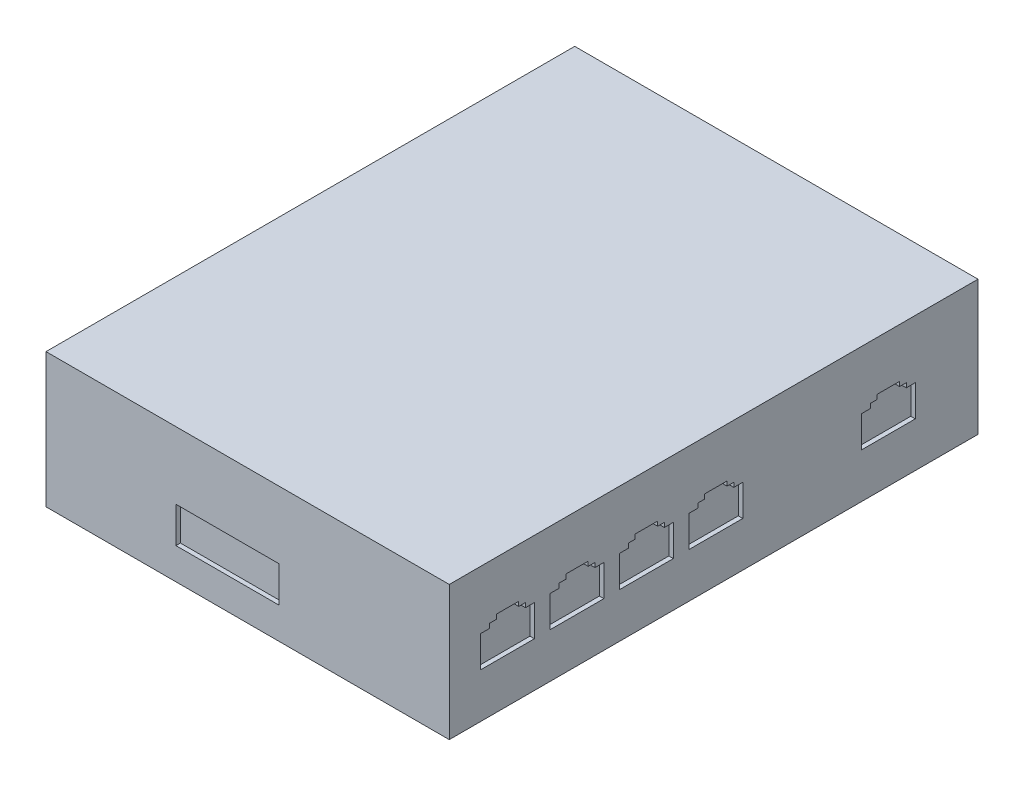
SolidWorks part; units mm, degrees
ref_plane "前视基准面" through (0, 0, 0) normal (0, 0, 1) x (1, 0, 0)
ref_plane "上视基准面" through (0, 0, 0) normal (0, 1, 0) x (1, 0, 0)
ref_plane "右视基准面" through (0, 0, 0) normal (1, 0, 0) x (0, 0, -1)
sketch "草图1" plane through (0, 0, 0) normal (0, 1, 0) x (1, 0, 0)
  line L1 (45, -59) -> (-45, -59)
  line L2 (45, -59) -> (45, 59)
  line L3 (45, 59) -> (-45, 59)
  line L4 (-45, -59) -> (-45, 59)
  line L5 (45, -59) -> (-45, 59) construction
  line L6 (45, 59) -> (-45, -59) construction
  point P0 (0, 0)
  dimension "D1" = 90
  dimension "D2" = 118
extrude "凸台-拉伸1" add sketch "草图1" along normal blind 30
hole_wizard "M3 螺纹孔的螺纹孔钻头1" positions "草图3" profile "草图4" hole size "M3" standard "GB"
sketch "草图3" plane through (-45, 0, 0) normal (-1, 0, 0) x (0, 0, 1)
  line L0 (0, 0) -> (0, 30) construction
  line L1 (-59, 30) -> (59, 30) construction
  line L3 (59, 15) -> (-59, 15) construction
  line L4 (59, 30) -> (59, 0) construction
  line L5 (-59, 30) -> (-59, 0) construction
  point P0 (10, 15)
  point P2 (-10, 15)
  dimension "D1" = 20
sketch "草图4" plane through (-45, 15, 10) normal (0, 1, 0) x (0, 0, 1)
  line L0 (0, 0) -> (0, 5.7511)
  line L1 (0, 5.7511) -> (1.25, 5)
  line L2 (1.25, 5) -> (1.25, 0)
  line L5 (1.25, 0) -> (0, 0)
  line L10 (0, 5.7511) -> (-1.25, 5) construction
  line L11 (0, -6.35) -> (0, 107.95) construction
  dimension "孔直径" = 2.5
  dimension "孔深度" = 5
  dimension "导头角度" = 118
sketch "草图5" plane through (0, 0, 59) normal (0, 0, 1) x (1, 0, 0)
  line L0 (-45, 30) -> (-45, 0) construction
  line L1 (-16, 15) -> (7, 15)
  line L2 (-16, 15) -> (-16, 7)
  line L3 (-16, 7) -> (7, 7)
  line L4 (7, 15) -> (7, 7)
  line L5 (-45, 0) -> (45, 0) construction
  dimension "D1" = 23
  dimension "D2" = 8
  dimension "D3" = 29
  dimension "D4" = 7
extrude "切除-拉伸1" cut sketch "草图5" against normal blind 1
sketch "草图6" plane through (45, 0, 0) normal (1, 0, 0) x (0, 0, -1)
  line L0 (-46, 13.5) -> (-46, 24.7712) construction
  line L1 (-40, 10) -> (-52, 10)
  line L2 (-40, 10) -> (-40, 17)
  line L3 (-40, 17) -> (-42, 17)
  line L4 (-52, 10) -> (-52, 17)
  line L5 (-40, 10) -> (-52, 17) construction
  line L6 (-40, 17) -> (-52, 10) construction
  line L7 (-59, 0) -> (59, 0) construction
  line L8 (-50, 17) -> (-50, 18)
  line L9 (-50, 18) -> (-48.5, 18)
  line L10 (-42, 17) -> (-42, 18)
  line L11 (-50, 17) -> (-52, 17)
  line L12 (-59, 30) -> (-59, 0) construction
  line L13 (-48.5, 18) -> (-48.5, 19)
  line L14 (-48.5, 19) -> (-43.5, 19)
  line L15 (-43.5, 18) -> (-43.5, 19)
  line L16 (-43.5, 18) -> (-42, 18)
  line L17 (-24.5, 10) -> (-36.5, 10)
  line L18 (-24.5, 10) -> (-24.5, 17)
  line L19 (-24.5, 17) -> (-26.5, 17)
  line L20 (-26.5, 17) -> (-26.5, 18)
  line L21 (-28, 18) -> (-26.5, 18)
  line L22 (-28, 18) -> (-28, 19)
  line L23 (-33, 19) -> (-28, 19)
  line L24 (-33, 18) -> (-33, 19)
  line L25 (-34.5, 18) -> (-33, 18)
  line L26 (-34.5, 17) -> (-34.5, 18)
  line L27 (-34.5, 17) -> (-36.5, 17)
  line L28 (-36.5, 10) -> (-36.5, 17)
  line L29 (-9, 10) -> (-21, 10)
  line L30 (-9, 10) -> (-9, 17)
  line L31 (-9, 17) -> (-11, 17)
  line L32 (-11, 17) -> (-11, 18)
  line L33 (-12.5, 18) -> (-11, 18)
  line L34 (-12.5, 18) -> (-12.5, 19)
  line L35 (-17.5, 19) -> (-12.5, 19)
  line L36 (-17.5, 18) -> (-17.5, 19)
  line L37 (-19, 18) -> (-17.5, 18)
  line L38 (-19, 17) -> (-19, 18)
  line L39 (-19, 17) -> (-21, 17)
  line L40 (-21, 10) -> (-21, 17)
  line L41 (6.5, 10) -> (-5.5, 10)
  line L42 (6.5, 10) -> (6.5, 17)
  line L43 (6.5, 17) -> (4.5, 17)
  line L44 (4.5, 17) -> (4.5, 18)
  line L45 (3, 18) -> (4.5, 18)
  line L46 (3, 18) -> (3, 19)
  line L47 (-2, 19) -> (3, 19)
  line L48 (-2, 18) -> (-2, 19)
  line L49 (-3.5, 18) -> (-2, 18)
  line L50 (-3.5, 17) -> (-3.5, 18)
  line L51 (-3.5, 17) -> (-5.5, 17)
  line L52 (-5.5, 10) -> (-5.5, 17)
  line L53 (33, 10) -> (33, 17)
  line L54 (35, 17) -> (33, 17)
  line L55 (35, 17) -> (35, 18)
  line L56 (35, 18) -> (36.5, 18)
  line L57 (36.5, 18) -> (36.5, 19)
  line L58 (36.5, 19) -> (41.5, 19)
  line L59 (41.5, 18) -> (41.5, 19)
  line L60 (41.5, 18) -> (43, 18)
  line L61 (43, 17) -> (43, 18)
  line L62 (45, 17) -> (43, 17)
  line L63 (45, 10) -> (45, 17)
  line L64 (45, 10) -> (33, 10)
  point P0 (-46, 13.5)
  dimension "D1" = 7
  dimension "D2" = 12
  dimension "D3" = 1
  dimension "D4" = 8
  dimension "D5" = 5
  dimension "D6" = 1
  dimension "D7" = 10
  dimension "D8" = 7
  dimension "D9" = 4
  dimension "D10" = 2
extrude "切除-拉伸2" cut sketch "草图6" against normal blind 1
